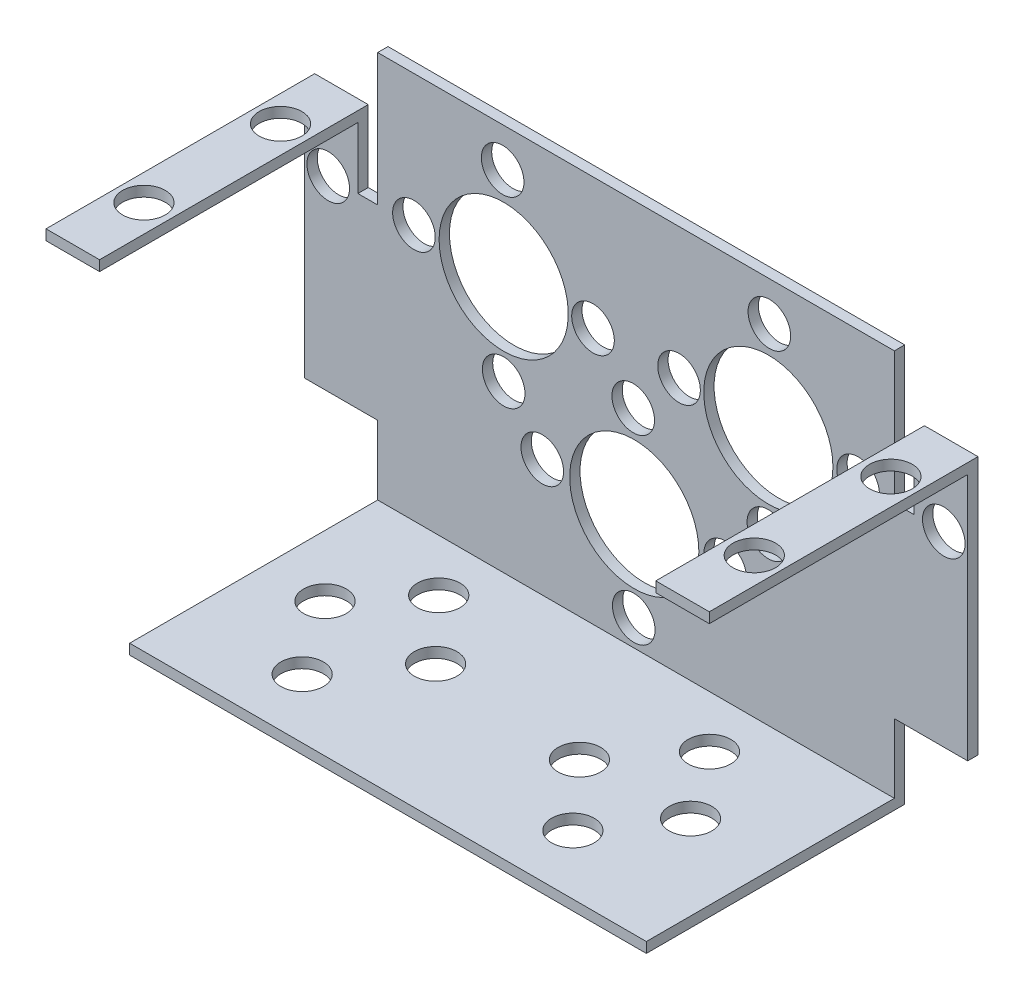
SolidWorks part; units mm, degrees
ref_plane "Front Plane" through (0, 0, 0) normal (0, 0, 1) x (1, 0, 0)
ref_plane "Top Plane" through (0, 0, 0) normal (0, 1, 0) x (1, 0, 0)
ref_plane "Right Plane" through (0, 0, 0) normal (1, 0, 0) x (0, 0, -1)
sketch "Sketch1" plane through (0, 0, 0) normal (0, 1, 0) x (1, 0, 0)
  line L1 (-42.6187, -15.2936) -> (-22.6187, -15.2936)
  line L2 (-42.6187, -15.2936) -> (-42.6187, -35.2936)
  line L3 (-42.6187, -35.2936) -> (-22.6187, -35.2936)
  line L4 (-22.6187, -15.2936) -> (-22.6187, -35.2936)
  dimension "D1" = 20
  dimension "D2" = 20
extrude "Boss-Extrude1" add sketch "Sketch1" along normal blind 0.8
sketch "Sketch2" plane through (0, 0.8, 0) normal (0, 1, 0) x (1, 0, 0)
  line L0 (-22.6187, -35.2936) -> (-22.6187, -15.2936) construction
  line L1 (-42.6187, -15.2936) -> (-22.6187, -15.2936)
  line L2 (-42.6187, -15.2936) -> (-42.6187, -16.0936)
  line L3 (-42.6187, -16.0936) -> (-22.6187, -16.0936)
  line L4 (-22.6187, -15.2936) -> (-22.6187, -16.0936)
  dimension "D1" = 0.8
extrude "Boss-Extrude2" add sketch "Sketch2" along normal blind 30 contours L2 L1 L4 L3
sketch "Sketch3" plane through (0, 0, 16.0936) normal (0, 0, 1) x (1, 0, 0)
  line L0 (-22.6187, 30.8) -> (-22.6187, 0.8) construction
  line L1 (-22.6187, 26.1441) -> (-16.9447, 26.1441)
  line L2 (-22.6187, 26.1441) -> (-22.6187, 6.1441)
  line L3 (-22.6187, 6.1441) -> (-16.9447, 6.1441)
  line L4 (-16.9447, 26.1441) -> (-16.9447, 6.1441)
  dimension "D1" = 20
extrude "Boss-Extrude3" add sketch "Sketch3" against normal blind 0.8 contours L2 L1 L4 L3
sketch "Sketch4" plane through (0, 0, 16.0936) normal (0, 0, 1) x (1, 0, 0)
  line L2 (-22.6187, 26.1441) -> (-21.0904, 26.1441)
  line L3 (-22.6187, 26.1441) -> (-22.6187, 20.5813)
  line L4 (-22.6187, 20.5813) -> (-21.0904, 20.5813)
  line L5 (-21.0904, 26.1441) -> (-21.0904, 20.5813)
extrude "Cut-Extrude1" cut sketch "Sketch4" against normal blind 0.8
sketch "Sketch5" plane through (0, 0, 16.0936) normal (0, 0, 1) x (1, 0, 0)
  line L0 (-16.9447, 26.1441) -> (-16.9447, 6.1441) construction
  line L2 (-21.0904, 26.1441) -> (-16.9447, 26.1441)
  line L3 (-21.0904, 26.1441) -> (-21.0904, 25.3441)
  line L4 (-21.0904, 25.3441) -> (-16.9447, 25.3441)
  line L5 (-16.9447, 26.1441) -> (-16.9447, 25.3441)
  dimension "D1" = 0.8
extrude "Boss-Extrude4" add sketch "Sketch5" along normal blind 20 contours L3 L2 L5 L4
sketch "Sketch6" plane through (0, 0, 16.0936) normal (0, 0, 1) x (1, 0, 0)
  circle A0 centre (-32.3748, 20.6432) radius 5
  circle A2 centre (-25.4275, 20.6432) radius 1.65
  circle A3 centre (-32.2953, 27.7678) radius 1.65
  circle A4 centre (-32.3748, 13.6296) radius 1.65
  circle A5 centre (-39.2877, 20.6432) radius 1.65
  circle A6 centre (-18.7925, 20.6003) radius 1.65
  dimension "D1" = 10
  dimension "D2" = 3.3
  dimension "D3" = 3.3
  dimension "D4" = 3.3
  dimension "D5" = 3.3
extrude "Cut-Extrude2" cut sketch "Sketch6" against normal blind 20
mirror "Mirror1" about plane through (-42.6187, 0.8, 15.2936) normal (1, 0, 0) of bodies 108
sketch "Sketch7" plane through (0, 0, 16.0936) normal (0, 0, 1) x (1, 0, 0)
  circle A0 centre (-42.754, 9.7816) radius 5
  circle A1 centre (-42.8331, 16.853) radius 1.65
  circle A2 centre (-35.7164, 9.8607) radius 1.65
  circle A3 centre (-49.8751, 9.9003) radius 1.65
  circle A4 centre (-42.7935, 2.8187) radius 1.65
  dimension "D1" = 10
  dimension "D2" = 3.3
  dimension "D3" = 3.3
  dimension "D4" = 3.3
  dimension "D5" = 3.3
extrude "Cut-Extrude3" cut sketch "Sketch7" against normal blind 20
sketch "Sketch8" plane through (0, 26.1441, 0) normal (0, 1, 0) x (1, 0, 0)
  circle A0 centre (-66.2559, -19.9757) radius 1.65
  circle A1 centre (-66.2559, -30.5503) radius 1.65
  circle A2 centre (-18.9816, -19.9997) radius 1.65
  circle A3 centre (-18.9816, -30.5742) radius 1.65
  circle A4 centre (-53.8631, -20.1203) radius 1.65
  circle A5 centre (-53.8631, -30.6948) radius 1.65
  circle A6 centre (-32.9055, -20.1203) radius 1.65
  circle A7 centre (-32.9055, -30.6948) radius 1.65
  circle A10 centre (-57.8729, -24.917) radius 1.65
  circle A12 centre (-49.3896, -24.8358) radius 1.65
  circle A15 centre (-37.4003, -25.6922) radius 1.65
  circle A17 centre (-29.1479, -25.3418) radius 1.65
  dimension "D1" = 3.3
extrude "Cut-Extrude4" cut sketch "Sketch8" against normal blind 50
